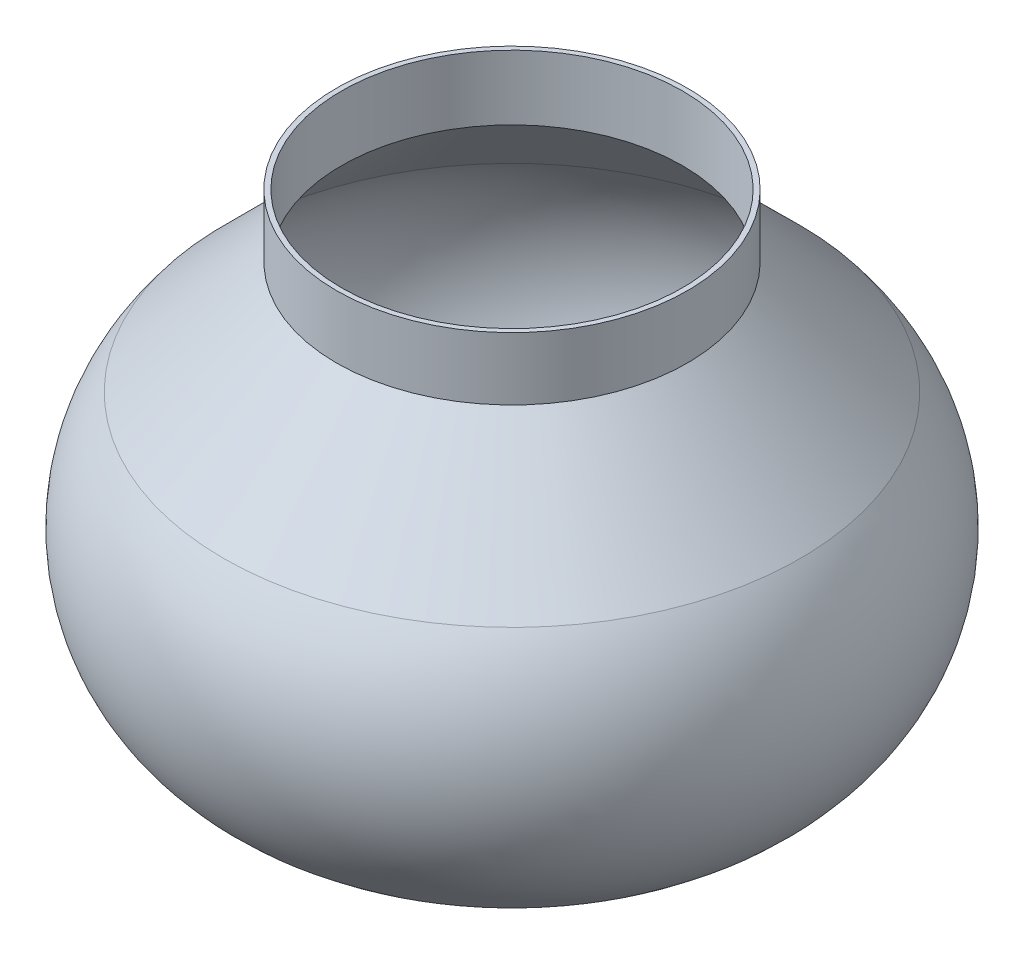
SolidWorks part; units mm, degrees
ref_plane "Front" through (0, 0, 0) normal (0, 0, 1) x (1, 0, 0)
ref_plane "Top" through (0, 0, 0) normal (0, 1, 0) x (1, 0, 0)
ref_plane "Right" through (0, 0, 0) normal (1, 0, 0) x (0, 0, -1)
sketch "Sketch1" plane through (0, 0, 0) normal (0, 0, 1) x (1, 0, 0)
  line L0 (0, 167.64) -> (0, -48.1974) construction
  line L1 (0, 0) -> (71.12, 0)
  line L2 (-49.6584, 167.64) -> (191.8729, 167.64) construction
  line L3 (116.84, 121.9328) -> (71.1072, 167.64)
  line L4 (71.1072, 167.64) -> (71.1072, 193.04)
  line L5 (69.1072, 166.8112) -> (69.1072, 193.04)
  line L6 (115.3502, 120.5941) -> (69.1072, 166.8112)
  line L7 (0, 2) -> (70.9441, 2)
  line L8 (69.1072, 193.04) -> (71.1072, 193.04)
  line L9 (0, 0) -> (0, 2)
  arc A0 (71.12, 0) -> (116.84, 121.9328) centre (58.0136, 74.4524) ccw
  arc A1 (70.9441, 2) -> (115.3502, 120.5941) centre (58.0136, 74.4524) ccw
  dimension "D2" = 75.5972
  dimension "D1" = 71.12
  dimension "D3" = 116.84
  dimension "D4" = 58.0136
  dimension "D5" = 167.64
  dimension "D6" = 25.4
  dimension "D7" = 64.6578
  dimension "D8" = 2
revolve "Revolve1" add sketch "Sketch1" angle 360 about L0
